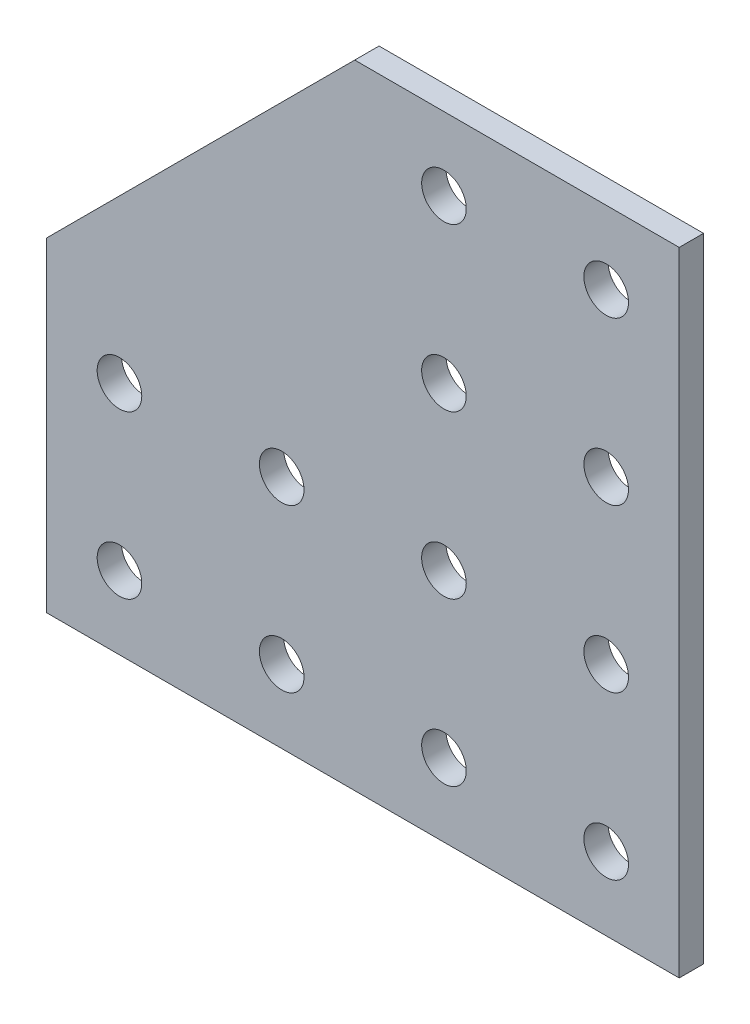
SolidWorks part; units mm, degrees
ref_plane "Front" through (0, 0, 0) normal (0, 0, 1) x (1, 0, 0)
ref_plane "Top" through (0, 0, 0) normal (0, 1, 0) x (1, 0, 0)
ref_plane "Right" through (0, 0, 0) normal (1, 0, 0) x (0, 0, -1)
sketch "Esquisse1" plane through (0, 0, 0) normal (0, 0, 1) x (1, 0, 0)
  line L0 (0, 0) -> (0, 40)
  line L1 (0, 40) -> (38, 78)
  line L2 (38, 78) -> (78, 78)
  line L3 (78, 78) -> (78, 0)
  line L4 (78, 0) -> (0, 0)
  line L5 (78, 0) -> (19, 59) construction
  line L6 (0, 19) -> (78, 19) construction
  line L7 (19, 19) -> (19, 9.3162) construction
  line L8 (39, 19) -> (39, 26.7589) construction
  line L9 (59, 19) -> (59, 9.3162) construction
  line L10 (59, 59) -> (68.6838, 59) construction
  circle A0 centre (9, 29) radius 2.75
  circle A1 centre (9, 9) radius 2.75
  circle A2 centre (29, 9) radius 2.75
  circle A3 centre (29, 29) radius 2.75
  circle A4 centre (49, 29) radius 2.75
  circle A5 centre (49, 9) radius 2.75
  circle A6 centre (69, 9) radius 2.75
  circle A7 centre (69, 29) radius 2.75
  circle A8 centre (49, 49) radius 2.75
  circle A9 centre (69, 49) radius 2.75
  circle A10 centre (69, 69) radius 2.75
  circle A11 centre (49, 69) radius 2.75
  dimension "D6" = 5.5
  dimension "D1" = 78
  dimension "D2" = 78
  dimension "D3" = 20
  dimension "D4" = 9
  dimension "D5" = 9
  dimension "D7" = 20
  dimension "D8" = 20
  dimension "D9" = 40
extrude "Boss.-Extru.1" add sketch "Esquisse1" along normal blind 3
